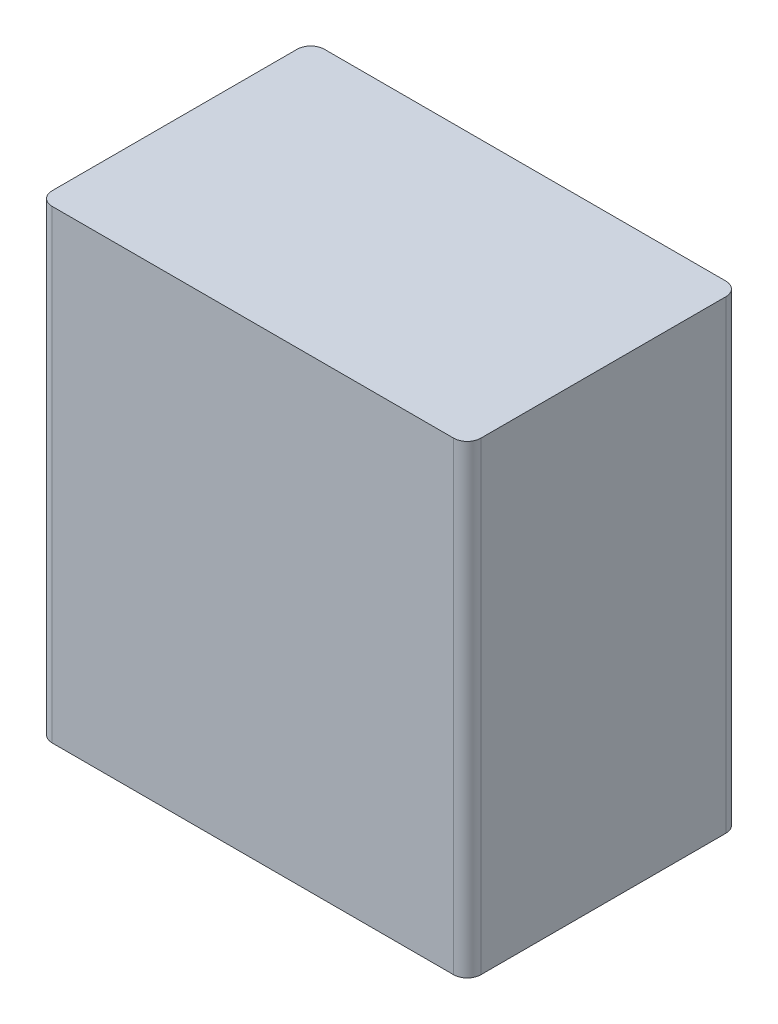
SolidWorks part; units mm, degrees
ref_plane "前视基准面" through (0, 0, 0) normal (0, 0, 1) x (1, 0, 0)
ref_plane "上视基准面" through (0, 0, 0) normal (0, 1, 0) x (1, 0, 0)
ref_plane "右视基准面" through (0, 0, 0) normal (1, 0, 0) x (0, 0, -1)
other "Configuration Table"
sketch "草图1" plane through (0, 0, 0) normal (0, 0, 1) x (1, 0, 0)
  line L0 (0, 0) -> (63, 0)
  line L1 (63, 0) -> (63, 68.3)
  line L2 (63, 68.3) -> (0, 68.3)
  line L3 (0, 68.3) -> (0, 0)
  dimension "width" = 63
  dimension "height" = 68.3
extrude "BlockExtrude" add sketch "草图1" along normal blind 40
fillet "Fillet" radius 2 4 edges at (0, 34.15, 0) (63, 34.15, 0) (0, 34.15, 40) (63, 34.15, 40)
